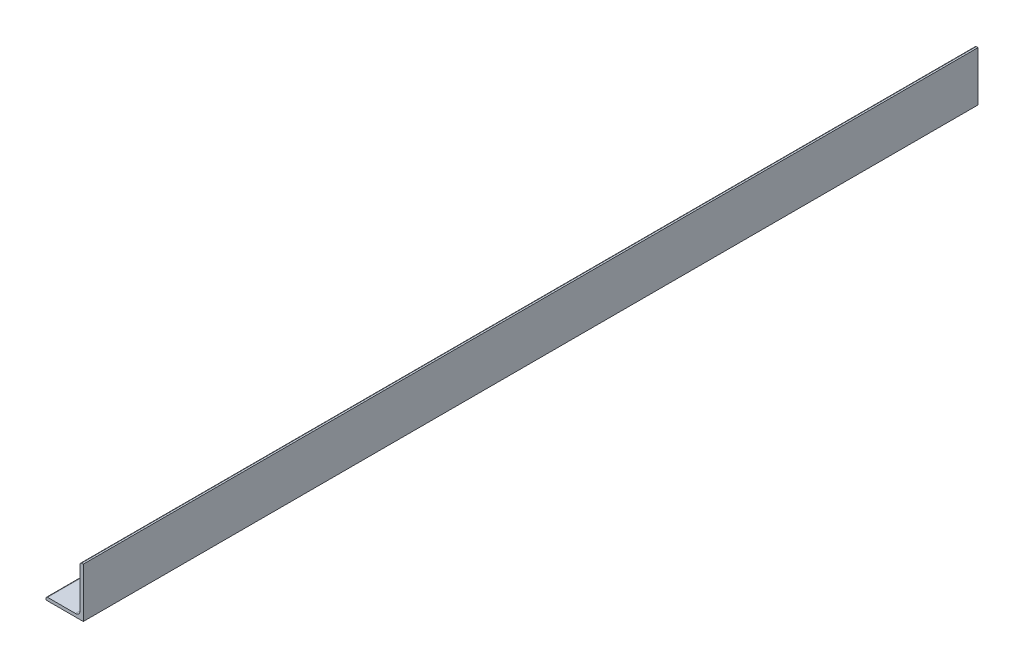
SolidWorks part; units mm, degrees
ref_plane "Front Plane" through (0, 0, 0) normal (0, 0, 1) x (1, 0, 0)
ref_plane "Top Plane" through (0, 0, 0) normal (0, 1, 0) x (1, 0, 0)
ref_plane "Right Plane" through (0, 0, 0) normal (1, 0, 0) x (0, 0, -1)
sketch "Sketch0" plane through (0, 0, 0) normal (0, 0, 1) x (1, 0, 0)
  line L0 (-19.05, -25.4) -> (19.05, -25.4)
  line L1 (19.05, -25.4) -> (19.05, 25.4)
  line L2 (19.05, 0) -> (0, 0) construction
  line L3 (0, 0) -> (0, -25.4) construction
  line L4 (15.875, -17.4498) -> (15.875, 25.4) construction
  line L5 (11.0998, -22.225) -> (-19.05, -22.225) construction
  arc A0 (15.875, -17.4498) -> (11.0998, -22.225) centre (11.0998, -17.4498) cw
  point P3 (14.4764, -20.8264)
  dimension "Inside Corner Radius" = 4.7752
  dimension "Outside Height" = 50.8
  dimension "Inside Height" = 47.625
  dimension "Inside Width" = 34.925
  dimension "Wall Thickness" = 3.175
  dimension "D1" = 3.175
  dimension "Outside Width" = 38.1
sketch "Sketch1" plane through (0, 0, 0) normal (1, 0, 0) x (0, 0, -1)
  line L0 (457.2, 0) -> (-457.2, 0)
  point P4 (0, 0)
  dimension "Length" = 914.4
sketch "Sketch2" plane through (0, 0, 0) normal (0, 0, 1) x (1, 0, 0)
  line L0 (-19.05, -25.4) -> (19.05, -25.4)
  line L1 (19.05, -25.4) -> (19.05, 25.4)
  line L2 (19.05, 25.4) -> (15.875, 25.4) construction
  line L3 (15.875, 23.8125) -> (15.875, -17.4498)
  line L4 (11.0998, -22.225) -> (-17.4625, -22.225)
  line L5 (-19.05, -25.4) -> (-19.05, -22.225) construction
  line L6 (17.4625, 25.4) -> (19.05, 25.4)
  line L7 (-19.05, -23.8125) -> (-19.05, -25.4)
  line L8 (19.05, 0) -> (0, 0) construction
  line L9 (0, 0) -> (0, -25.4) construction
  arc A0 (15.875, 23.8125) -> (17.4625, 25.4) centre (17.4625, 23.8125) cw
  arc A1 (-19.05, -23.8125) -> (-17.4625, -22.225) centre (-17.4625, -23.8125) cw
  arc A2 (15.875, -17.4498) -> (11.0998, -22.225) centre (11.0998, -17.4498) cw
  dimension "Inside Radius" = 4.7752
  dimension "Height" = 50.8
  dimension "Width" = 38.1
  dimension "Thickness" = 3.175
extrude "Boss-Extrude1" add sketch "Sketch2" along normal mid plane 914.4
sketch "Break Locations" plane through (0, 0, 0) normal (1, 0, 0) x (0, 0, -1)
  line L0 (-405.384, 0) -> (405.384, 0)
  line L1 (-457.2, -25.4) -> (-457.2, 25.4) construction
  line L2 (457.2, -25.4) -> (457.2, 25.4) construction
  point P0 (-414.02, 0)
  point P1 (414.02, 0)
  point P10 (0, 0)
  point P11 (405.384, 0)
  point P13 (-405.384, 0)
  dimension "D1" = 43.18
  dimension "D2" = 43.18
  dimension "D3" = 51.816
equation "\"D1@Break Locations\" = .85 * \"Height@Sketch2\""
equation "\"D2@Break Locations\"=\"D1@Break Locations\""
equation "\"Thickness@Sketch2\"=\"wall thickness@sketch0\""
equation "\"Height@Sketch2\"=\"outside height@sketch0\""
equation "\"Width@Sketch2\"=\"outside width@sketch0\""
equation "\"Inside Radius@Sketch2\"=\"inside corner radius@sketch0\""
equation "\"Length@Boss-Extrude1\"=\"length@sketch1\""
equation "\"D3@Break Locations\"=\"D2@Break Locations\"*1.2"
equation "\"D1@Sketch0\"=\"Wall Thickness@Sketch0\""
